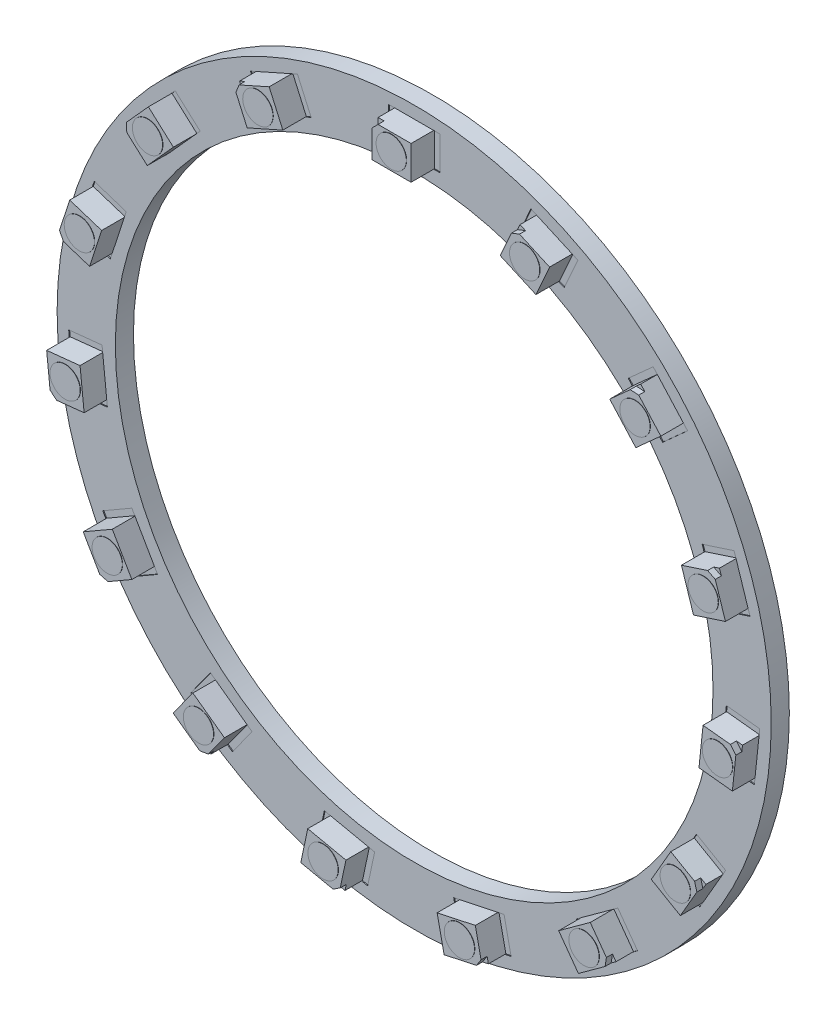
SolidWorks part; units mm, degrees
ref_plane "Front Plane" through (0, 0, 0) normal (0, 0, 1) x (1, 0, 0)
ref_plane "Top Plane" through (0, 0, 0) normal (0, 1, 0) x (1, 0, 0)
ref_plane "Right Plane" through (0, 0, 0) normal (1, 0, 0) x (0, 0, -1)
sketch "Sketch1" plane through (0, 0, 0) normal (0, 0, 1) x (1, 0, 0)
  line L0 (0, 25.085) -> (0, 29.972) construction
  circle A0 centre (0, 0) radius 29.972
  circle A1 centre (0, 0) radius 25.085
  circle A2 centre (0, 0) radius 27.5285 construction
  point P6 (0, 27.5285)
  dimension "D1" = 59.944
  dimension "D2" = 50.17
extrude "Boss-Extrude1" add sketch "Sketch1" along normal blind 1.52
sketch "Sketch2" plane through (0, 0, 1.52) normal (0, 0, 1) x (1, 0, 0)
  line L0 (0, 25.085) -> (0, 29.972) construction
  line L2 (-1.6383, 26.1188) -> (1.6383, 26.1188)
  line L3 (-1.6383, 26.1188) -> (-1.6383, 28.9382)
  line L4 (-1.6383, 28.9382) -> (1.6383, 28.9382)
  line L5 (1.6383, 26.1188) -> (1.6383, 28.9382)
  line L6 (-1.6383, 26.1188) -> (1.6383, 28.9382) construction
  line L7 (-1.6383, 28.9382) -> (1.6383, 26.1188) construction
  circle A0 centre (0, 0) radius 25.085 construction
  circle A1 centre (0, 0) radius 29.972 construction
  circle A2 centre (0, 0) radius 27.5285 construction
  point P7 (0, 27.5285)
  point P11 (0, 27.5285)
  dimension "D1" = 3.2766
  dimension "D2" = 2.8194
extrude "Boss-Extrude2" add sketch "Sketch2" along normal blind 1.9
sketch "Sketch3" plane through (0, 0, 3.42) normal (0, 0, 1) x (1, 0, 0)
  line L0 (-1.6383, 28.4302) -> (-1.1303, 28.9382)
  line L1 (-1.6383, 28.9382) -> (-1.6383, 26.1188) construction
  line L2 (1.6383, 28.9382) -> (-1.6383, 28.9382) construction
  line L3 (-1.1303, 28.9382) -> (-1.6383, 28.9382)
  line L4 (-1.6383, 28.9382) -> (-1.6383, 28.4302)
  dimension "D1" = 0.508
  dimension "D2" = 0.508
extrude "Cut-Extrude3" cut sketch "Sketch3" against normal blind 0.508
sketch "Sketch5" plane through (0, 0, 3.42) normal (0, 0, 1) x (1, 0, 0)
  line L0 (0, 26.1188) -> (0, 28.9382) construction
  line L1 (-1.6383, 26.1188) -> (1.6383, 26.1188) construction
  line L2 (1.6383, 28.9382) -> (-1.1303, 28.9382) construction
  circle A0 centre (0, 27.5285) radius 1.27
  dimension "D1" = 2.54
extrude "Boss-Extrude4" add sketch "Sketch5" along normal blind 0.0254
sketch "Sketch6" plane through (0, 0, 1.52) normal (0, 0, 1) x (1, 0, 0)
  line L0 (1.6383, 28.9382) -> (2.159, 28.9382)
  line L3 (-1.6383, 28.9382) -> (-1.6383, 26.1188)
  line L4 (-2.159, 26.1188) -> (-1.6383, 26.1188)
  line L5 (-2.159, 26.1188) -> (-2.159, 28.9382)
  line L6 (-2.159, 28.9382) -> (-1.6383, 28.9382)
  line L7 (2.159, 26.1188) -> (2.159, 28.9382)
  line L9 (1.6383, 26.1188) -> (2.159, 26.1188)
  line L10 (1.6383, 26.1188) -> (1.6383, 28.9382)
  point P6 (0, 29.2125)
  dimension "D1" = 4.318
  dimension "D2" = 0.5207
extrude "Cut-Extrude8" cut sketch "Sketch6" against normal blind 0.0762
pattern_circular "CirPattern1" count 15 over 360 about axis through (0, 0, 0) along (0, 0, 1) of "Boss-Extrude2"
pattern_circular "CirPattern2" count 15 over 360 about axis through (0, 0, 0) along (0, 0, 1) of "Cut-Extrude3"
pattern_circular "CirPattern3" count 15 over 360 about axis through (0, 0, 0) along (0, 0, 1) of "Boss-Extrude4"
pattern_circular "CirPattern4" count 15 over 360 about axis through (0, 0, 0) along (0, 0, 1) of "Cut-Extrude8"
